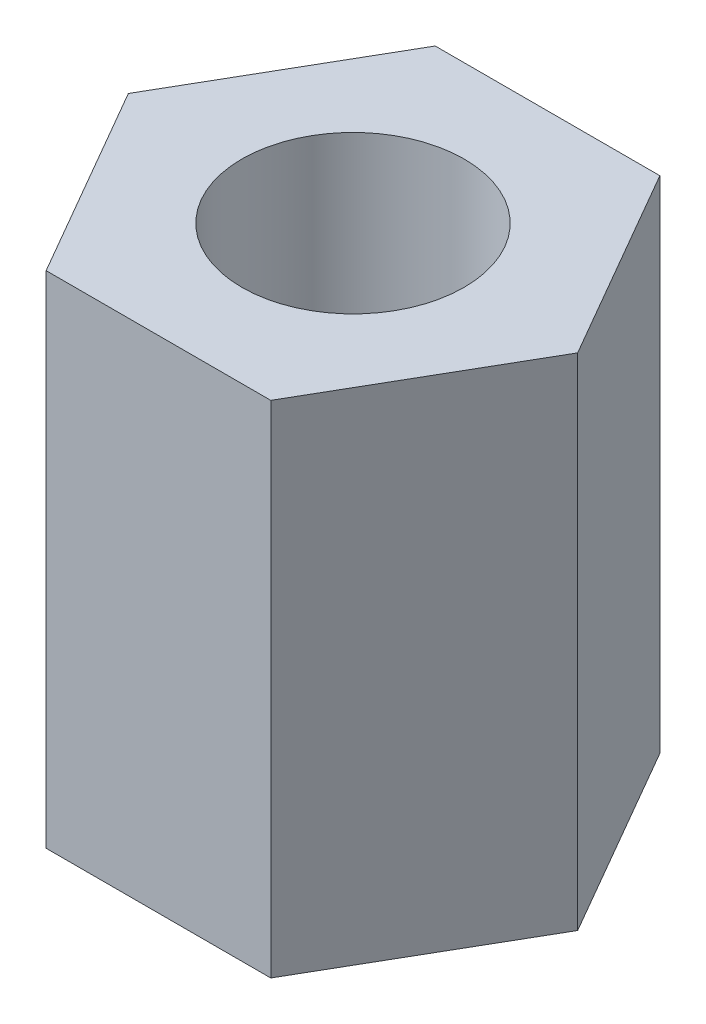
SolidWorks part; units mm, degrees
material "Brass"
ref_plane "前视基准面" through (0, 0, 0) normal (0, 0, 1) x (1, 0, 0)
ref_plane "上视基准面" through (0, 0, 0) normal (0, 1, 0) x (1, 0, 0)
ref_plane "右视基准面" through (0, 0, 0) normal (1, 0, 0) x (0, 0, -1)
sketch "Sketch1" plane through (0, 0, 0) normal (0, 1, 0) x (1, 0, 0)
  line L1 (4.0415, 0) -> (2.0207, 3.5)
  line L2 (2.0207, 3.5) -> (-2.0207, 3.5)
  line L3 (-2.0207, 3.5) -> (-4.0415, 0)
  line L4 (-4.0415, 0) -> (-2.0207, -3.5)
  line L5 (-2.0207, -3.5) -> (2.0207, -3.5)
  line L6 (2.0207, -3.5) -> (4.0415, 0)
  circle A0 centre (0, 0) radius 3.5 construction
  circle A1 centre (0, 0) radius 2
  dimension "D1" = 7
  dimension "D2" = 4
extrude "Boss-Extrude1" add sketch "Sketch1" along normal blind 9
